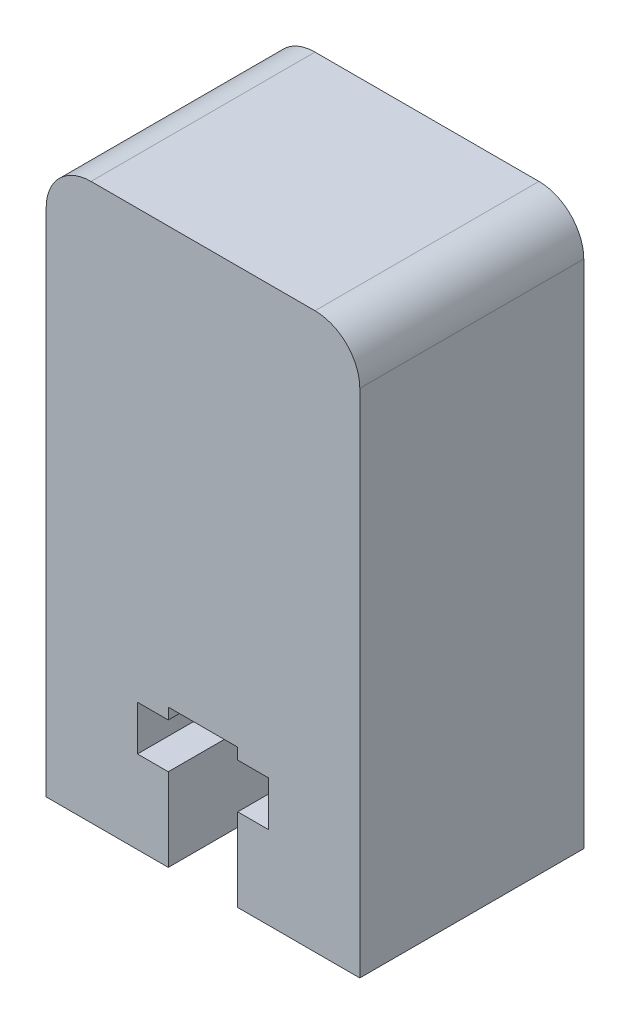
SolidWorks part; units mm, degrees
ref_plane "Płaszczyzna przednia" through (0, 0, 0) normal (0, 0, 1) x (1, 0, 0)
ref_plane "Płaszczyzna górna" through (0, 0, 0) normal (0, 1, 0) x (1, 0, 0)
ref_plane "Płaszczyzna prawa" through (0, 0, 0) normal (1, 0, 0) x (0, 0, -1)
sketch "Szkic1" plane through (0, 0, 0) normal (0, 0, 1) x (1, 0, 0)
  line L0 (-46.476, 4) -> (-60.476, 4)
  line L1 (-46.476, 4) -> (-46.476, 26.8)
  line L2 (-60.476, 4) -> (-60.476, 26.8)
  line L3 (-48.476, 28.8) -> (-58.476, 28.8)
  arc A0 (-60.476, 26.8) -> (-58.476, 28.8) centre (-58.476, 26.8) cw
  arc A1 (-46.476, 26.8) -> (-48.476, 28.8) centre (-48.476, 26.8) ccw
  dimension "D3" = 2
  dimension "D1" = 24.8
  dimension "D2" = 14
extrude "Dodanie-wyciągnięcie1" add sketch "Szkic1" along normal blind 10
sketch "Szkic3" plane through (0, 0, 10) normal (0, 0, 1) x (1, 0, 0)
  line L0 (-51.926, 4) -> (-55.026, 4)
  line L1 (-51.926, 4) -> (-51.926, 7.7)
  line L2 (-55.026, 4) -> (-55.026, 7.7)
  line L3 (-51.926, 10.2) -> (-55.026, 10.2)
  line L4 (-60.476, 4) -> (-46.476, 4) construction
  line L5 (-50.551, 7.7) -> (-50.551, 9.7)
  line L6 (-50.551, 7.7) -> (-51.926, 7.7)
  line L7 (-50.551, 9.7) -> (-51.926, 9.7)
  line L8 (-56.401, 7.7) -> (-56.401, 9.7)
  line L9 (-51.926, 9.7) -> (-51.926, 10.2)
  line L10 (-55.026, 7.7) -> (-56.401, 7.7)
  line L11 (-55.026, 9.7) -> (-55.026, 10.2)
  line L12 (-55.026, 9.7) -> (-56.401, 9.7)
  line L13 (-60.476, 26.8) -> (-60.476, 4) construction
  point P14 (-53.476, 4)
  dimension "D1" = 3.1
  dimension "D2" = 5.85
  dimension "D3" = 2
  dimension "D4" = 0.5
  dimension "D5" = 1.375
  dimension "D6" = 6.2
  dimension "D7" = 7
extrude "Wytnij-wyciągnięcie1" cut sketch "Szkic3" against normal blind 10
equation "\"tolerancja_wpusy\"=0.2"
equation "\"dlugosc_wpustu_duzy\"=20"
equation "\"srednica_otworu_M3\"=3.1"
equation "\"szerokosc_nogi_T\"=3.1"
equation "\"dlugosc_T_30\"=11"
equation "\"grubosc_na_nakretke_kwadrat\"=2"
equation "\"szerokosc_na_nakretke_kwadrat\"=5.85"
equation "\"wyokosc_nadstawki_T\"=0.5"
equation "\"dlugosc_T_20_6\"=14"
equation "\"D1@Szkic3\"=\"szerokosc_nogi_T\""
equation "\"D2@Szkic3\"=\"szerokosc_na_nakretke_kwadrat\""
equation "\"D3@Szkic3\"=\"grubosc_na_nakretke_kwadrat\""
equation "\"D4@Szkic3\"=\"wyokosc_nadstawki_T\""
equation "\"D5@Szkic3\"=(\"szerokosc_na_nakretke_kwadrat\"-\"szerokosc_nogi_T\")/2"
